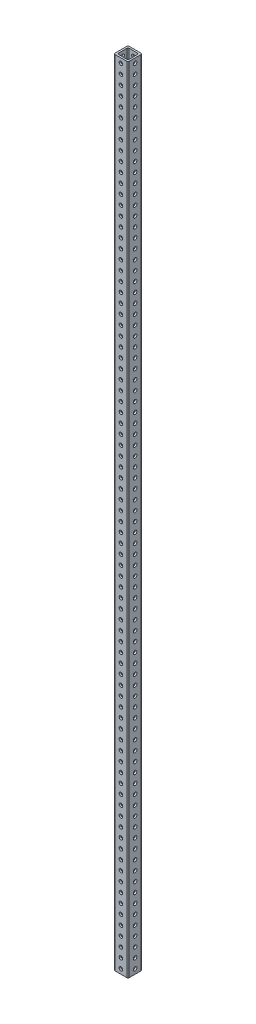
SolidWorks part; units mm, degrees
ref_plane "Front Plane" through (0, 0, 0) normal (0, 0, 1) x (1, 0, 0)
ref_plane "Top Plane" through (0, 0, 0) normal (0, 1, 0) x (1, 0, 0)
ref_plane "Right Plane" through (0, 0, 0) normal (1, 0, 0) x (0, 0, -1)
sketch "Sketch1" plane through (0, 0, 0) normal (0, 1, 0) x (1, 0, 0)
  line L0 (4.7625, -4.7625) -> (33.3375, -4.7625)
  line L1 (0, 0) -> (38.1, 0)
  line L2 (0, 0) -> (0, -38.1)
  line L3 (0, -38.1) -> (38.1, -38.1)
  line L4 (38.1, 0) -> (38.1, -38.1)
  line L5 (33.3375, -4.7625) -> (33.3375, -33.3375)
  line L6 (4.7625, -33.3375) -> (33.3375, -33.3375)
  line L7 (4.7625, -4.7625) -> (4.7625, -33.3375)
  dimension "D1" = 38.1
  dimension "D2" = 38.1
  dimension "D3" = 4.7625
extrude "Boss-Extrude1" add sketch "Sketch1" along normal blind 2133.6
fillet "Fillet1" radius 3.175 8 edges at (33.3375, 1066.8, 4.7625) (33.3375, 1066.8, 33.3375) (4.7625, 1066.8, 4.7625) (4.7625, 1066.8, 33.3375) (0, 1066.8, 0) (38.1, 1066.8, 0) (0, 1066.8, 38.1) (38.1, 1066.8, 38.1)
sketch "Sketch2" plane through (0, 0, 38.1) normal (0, 0, 1) x (1, 0, 0)
  line L0 (19.05, 2133.6) -> (19.05, 0) construction
  line L1 (3.175, 2133.6) -> (34.925, 2133.6) construction
  line L2 (3.175, 0) -> (34.925, 0) construction
  circle A0 centre (19.05, 2120.9) radius 4.7625
  circle A1 centre (19.05, 2095.5) radius 4.7625
  circle A2 centre (19.05, 2070.1) radius 4.7625
  circle A3 centre (19.05, 2044.7) radius 4.7625
  circle A4 centre (19.05, 2019.3) radius 4.7625
  circle A5 centre (19.05, 1993.9) radius 4.7625
  circle A6 centre (19.05, 1968.5) radius 4.7625
  circle A7 centre (19.05, 1943.1) radius 4.7625
  circle A8 centre (19.05, 1917.7) radius 4.7625
  circle A9 centre (19.05, 1892.3) radius 4.7625
  circle A10 centre (19.05, 1866.9) radius 4.7625
  circle A11 centre (19.05, 1841.5) radius 4.7625
  circle A12 centre (19.05, 1816.1) radius 4.7625
  circle A13 centre (19.05, 1790.7) radius 4.7625
  circle A14 centre (19.05, 1765.3) radius 4.7625
  circle A15 centre (19.05, 1739.9) radius 4.7625
  circle A16 centre (19.05, 1714.5) radius 4.7625
  circle A17 centre (19.05, 1689.1) radius 4.7625
  circle A18 centre (19.05, 1663.7) radius 4.7625
  circle A19 centre (19.05, 1638.3) radius 4.7625
  circle A20 centre (19.05, 1612.9) radius 4.7625
  circle A21 centre (19.05, 1587.5) radius 4.7625
  circle A22 centre (19.05, 1562.1) radius 4.7625
  circle A23 centre (19.05, 1536.7) radius 4.7625
  circle A24 centre (19.05, 1511.3) radius 4.7625
  circle A25 centre (19.05, 1485.9) radius 4.7625
  circle A26 centre (19.05, 1460.5) radius 4.7625
  circle A27 centre (19.05, 1435.1) radius 4.7625
  circle A28 centre (19.05, 1409.7) radius 4.7625
  circle A29 centre (19.05, 1384.3) radius 4.7625
  circle A30 centre (19.05, 1358.9) radius 4.7625
  circle A31 centre (19.05, 1333.5) radius 4.7625
  circle A32 centre (19.05, 1308.1) radius 4.7625
  circle A33 centre (19.05, 1282.7) radius 4.7625
  circle A34 centre (19.05, 1257.3) radius 4.7625
  circle A35 centre (19.05, 1231.9) radius 4.7625
  circle A36 centre (19.05, 1206.5) radius 4.7625
  circle A37 centre (19.05, 1181.1) radius 4.7625
  circle A38 centre (19.05, 1155.7) radius 4.7625
  circle A39 centre (19.05, 1130.3) radius 4.7625
  circle A40 centre (19.05, 1104.9) radius 4.7625
  circle A41 centre (19.05, 1079.5) radius 4.7625
  circle A42 centre (19.05, 1054.1) radius 4.7625
  circle A43 centre (19.05, 1028.7) radius 4.7625
  circle A44 centre (19.05, 1003.3) radius 4.7625
  circle A45 centre (19.05, 977.9) radius 4.7625
  circle A46 centre (19.05, 952.5) radius 4.7625
  circle A47 centre (19.05, 927.1) radius 4.7625
  circle A48 centre (19.05, 901.7) radius 4.7625
  circle A49 centre (19.05, 876.3) radius 4.7625
  circle A50 centre (19.05, 850.9) radius 4.7625
  circle A51 centre (19.05, 825.5) radius 4.7625
  circle A52 centre (19.05, 800.1) radius 4.7625
  circle A53 centre (19.05, 774.7) radius 4.7625
  circle A54 centre (19.05, 749.3) radius 4.7625
  circle A55 centre (19.05, 723.9) radius 4.7625
  circle A56 centre (19.05, 698.5) radius 4.7625
  circle A57 centre (19.05, 673.1) radius 4.7625
  circle A58 centre (19.05, 647.7) radius 4.7625
  circle A59 centre (19.05, 622.3) radius 4.7625
  circle A60 centre (19.05, 596.9) radius 4.7625
  circle A61 centre (19.05, 571.5) radius 4.7625
  circle A62 centre (19.05, 546.1) radius 4.7625
  circle A63 centre (19.05, 520.7) radius 4.7625
  circle A64 centre (19.05, 495.3) radius 4.7625
  circle A65 centre (19.05, 469.9) radius 4.7625
  circle A66 centre (19.05, 444.5) radius 4.7625
  circle A67 centre (19.05, 419.1) radius 4.7625
  circle A68 centre (19.05, 393.7) radius 4.7625
  circle A69 centre (19.05, 368.3) radius 4.7625
  circle A70 centre (19.05, 342.9) radius 4.7625
  circle A71 centre (19.05, 317.5) radius 4.7625
  circle A72 centre (19.05, 292.1) radius 4.7625
  circle A73 centre (19.05, 266.7) radius 4.7625
  circle A74 centre (19.05, 241.3) radius 4.7625
  circle A75 centre (19.05, 215.9) radius 4.7625
  circle A76 centre (19.05, 190.5) radius 4.7625
  circle A77 centre (19.05, 165.1) radius 4.7625
  circle A78 centre (19.05, 139.7) radius 4.7625
  circle A79 centre (19.05, 114.3) radius 4.7625
  circle A80 centre (19.05, 88.9) radius 4.7625
  circle A81 centre (19.05, 63.5) radius 4.7625
  circle A82 centre (19.05, 38.1) radius 4.7625
  circle A83 centre (19.05, 12.7) radius 4.7625
  dimension "D1" = 9.525
  dimension "D2" = 12.7
  dimension "D3" = 84
extrude "Cut-Extrude1" cut sketch "Sketch2" against normal blind 50.8
sketch "Sketch3" plane through (0, 0, 0) normal (-1, 0, 0) x (0, 0, 1)
  line L0 (19.05, 2133.6) -> (19.05, 0) construction
  line L1 (3.175, 2133.6) -> (34.925, 2133.6) construction
  line L2 (3.175, 0) -> (34.925, 0) construction
  circle A0 centre (19.05, 2120.9) radius 4.7625
  circle A1 centre (19.05, 2095.5) radius 4.7625
  circle A2 centre (19.05, 2070.1) radius 4.7625
  circle A3 centre (19.05, 2044.7) radius 4.7625
  circle A4 centre (19.05, 2019.3) radius 4.7625
  circle A5 centre (19.05, 1993.9) radius 4.7625
  circle A6 centre (19.05, 1968.5) radius 4.7625
  circle A7 centre (19.05, 1943.1) radius 4.7625
  circle A8 centre (19.05, 1917.7) radius 4.7625
  circle A9 centre (19.05, 1892.3) radius 4.7625
  circle A10 centre (19.05, 1866.9) radius 4.7625
  circle A11 centre (19.05, 1841.5) radius 4.7625
  circle A12 centre (19.05, 1816.1) radius 4.7625
  circle A13 centre (19.05, 1790.7) radius 4.7625
  circle A14 centre (19.05, 1765.3) radius 4.7625
  circle A15 centre (19.05, 1739.9) radius 4.7625
  circle A16 centre (19.05, 1714.5) radius 4.7625
  circle A17 centre (19.05, 1689.1) radius 4.7625
  circle A18 centre (19.05, 1663.7) radius 4.7625
  circle A19 centre (19.05, 1638.3) radius 4.7625
  circle A20 centre (19.05, 1612.9) radius 4.7625
  circle A21 centre (19.05, 1587.5) radius 4.7625
  circle A22 centre (19.05, 1562.1) radius 4.7625
  circle A23 centre (19.05, 1536.7) radius 4.7625
  circle A24 centre (19.05, 1511.3) radius 4.7625
  circle A25 centre (19.05, 1485.9) radius 4.7625
  circle A26 centre (19.05, 1460.5) radius 4.7625
  circle A27 centre (19.05, 1435.1) radius 4.7625
  circle A28 centre (19.05, 1409.7) radius 4.7625
  circle A29 centre (19.05, 1384.3) radius 4.7625
  circle A30 centre (19.05, 1358.9) radius 4.7625
  circle A31 centre (19.05, 1333.5) radius 4.7625
  circle A32 centre (19.05, 1308.1) radius 4.7625
  circle A33 centre (19.05, 1282.7) radius 4.7625
  circle A34 centre (19.05, 1257.3) radius 4.7625
  circle A35 centre (19.05, 1231.9) radius 4.7625
  circle A36 centre (19.05, 1206.5) radius 4.7625
  circle A37 centre (19.05, 1181.1) radius 4.7625
  circle A38 centre (19.05, 1155.7) radius 4.7625
  circle A39 centre (19.05, 1130.3) radius 4.7625
  circle A40 centre (19.05, 1104.9) radius 4.7625
  circle A41 centre (19.05, 1079.5) radius 4.7625
  circle A42 centre (19.05, 1054.1) radius 4.7625
  circle A43 centre (19.05, 1028.7) radius 4.7625
  circle A44 centre (19.05, 1003.3) radius 4.7625
  circle A45 centre (19.05, 977.9) radius 4.7625
  circle A46 centre (19.05, 952.5) radius 4.7625
  circle A47 centre (19.05, 927.1) radius 4.7625
  circle A48 centre (19.05, 901.7) radius 4.7625
  circle A49 centre (19.05, 876.3) radius 4.7625
  circle A50 centre (19.05, 850.9) radius 4.7625
  circle A51 centre (19.05, 825.5) radius 4.7625
  circle A52 centre (19.05, 800.1) radius 4.7625
  circle A53 centre (19.05, 774.7) radius 4.7625
  circle A54 centre (19.05, 749.3) radius 4.7625
  circle A55 centre (19.05, 723.9) radius 4.7625
  circle A56 centre (19.05, 698.5) radius 4.7625
  circle A57 centre (19.05, 673.1) radius 4.7625
  circle A58 centre (19.05, 647.7) radius 4.7625
  circle A59 centre (19.05, 622.3) radius 4.7625
  circle A60 centre (19.05, 596.9) radius 4.7625
  circle A61 centre (19.05, 571.5) radius 4.7625
  circle A62 centre (19.05, 546.1) radius 4.7625
  circle A63 centre (19.05, 520.7) radius 4.7625
  circle A64 centre (19.05, 495.3) radius 4.7625
  circle A65 centre (19.05, 469.9) radius 4.7625
  circle A66 centre (19.05, 444.5) radius 4.7625
  circle A67 centre (19.05, 419.1) radius 4.7625
  circle A68 centre (19.05, 393.7) radius 4.7625
  circle A69 centre (19.05, 368.3) radius 4.7625
  circle A70 centre (19.05, 342.9) radius 4.7625
  circle A71 centre (19.05, 317.5) radius 4.7625
  circle A72 centre (19.05, 292.1) radius 4.7625
  circle A73 centre (19.05, 266.7) radius 4.7625
  circle A74 centre (19.05, 241.3) radius 4.7625
  circle A75 centre (19.05, 215.9) radius 4.7625
  circle A76 centre (19.05, 190.5) radius 4.7625
  circle A77 centre (19.05, 165.1) radius 4.7625
  circle A78 centre (19.05, 139.7) radius 4.7625
  circle A79 centre (19.05, 114.3) radius 4.7625
  circle A80 centre (19.05, 88.9) radius 4.7625
  circle A81 centre (19.05, 63.5) radius 4.7625
  circle A82 centre (19.05, 38.1) radius 4.7625
  circle A83 centre (19.05, 12.7) radius 4.7625
  dimension "D2" = 9.525
  dimension "D1" = 12.7
  dimension "D3" = 84
extrude "Cut-Extrude2" cut sketch "Sketch3" against normal blind 50.8
